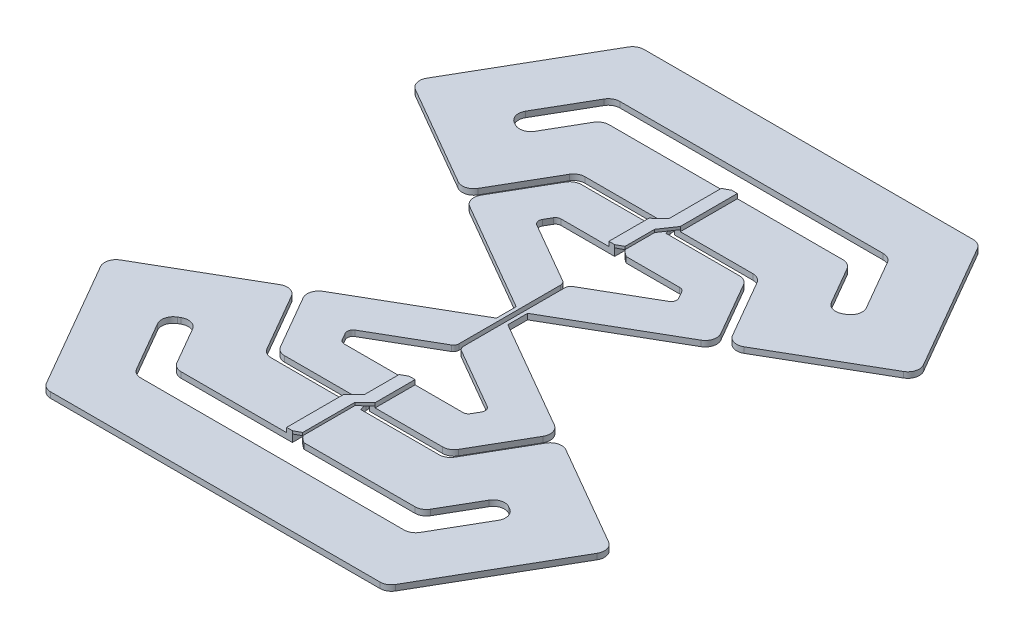
SolidWorks part; units mm, degrees
ref_plane "前视基准面" through (0, 0, 0) normal (0, 0, 1) x (1, 0, 0)
ref_plane "上视基准面" through (0, 0, 0) normal (0, 1, 0) x (1, 0, 0)
ref_plane "右视基准面" through (0, 0, 0) normal (1, 0, 0) x (0, 0, -1)
ref_plane "基准面1" through (0, 1, 0) normal (0, 1, 0) x (1, 0, 0)
ref_plane "基准面2" through (0, 1.3, 0) normal (0, 1, 0) x (1, 0, 0)
sketch "草图2" plane through (0, 0, 0) normal (0, 1, 0) x (1, 0, 0)
  line L0 (0, 9.4884) -> (0, -9.4884) construction
  line L1 (-1, -38.8119) -> (-1, 41.1881)
  line L3 (-1, 41.1881) -> (1, 41.1881)
  line L4 (1, -38.8119) -> (1, 41.1881)
  line L5 (-2.6411, -108.7811) -> (1, 41.1881) construction
  line L6 (-1, 41.1881) -> (2.6411, -108.7811) construction
  line L7 (-1, -38.8119) -> (1, -38.8119)
  point P1 (0, 0)
  point P4 (0, 0)
  dimension "D1" = 2
  dimension "D2" = 80
sketch "草图3" plane through (0, 0, 0) normal (0, 1, 0) x (1, 0, 0)
  line L0 (29.8397, 32.2391) -> (24.8038, 40.9615)
  line L1 (43.5, 28.5788) -> (30.5774, 50.9615)
  line L2 (28.8453, 51.9615) -> (-28.8453, 51.9615)
  line L3 (-30.5774, 50.9615) -> (-43.5, 28.5788)
  line L4 (-43.5, -28.5788) -> (-30.5774, -50.9615)
  line L5 (-28.8453, -51.9615) -> (28.8453, -51.9615)
  line L6 (30.5774, -50.9615) -> (43.5, -28.5788)
  line L7 (23, 12.1244) -> (22.5, 12.9904)
  line L8 (13.8453, 25.9808) -> (-13.8453, 25.9808)
  line L9 (-15.5774, 24.9808) -> (-21, 15.5885)
  line L10 (-21, -15.5885) -> (-15.5774, -24.9808)
  line L11 (-13.8453, -25.9808) -> (13.8453, -25.9808)
  line L12 (15.5774, -24.9808) -> (21, -15.5885)
  line L13 (0, 0) -> (0, 74.3259) construction
  line L14 (21, 15.5885) -> (15.5774, 24.9808)
  line L15 (45.5, -25.1147) -> (45.4917, -25.1099)
  line L16 (20.2679, -12.8564) -> (0, -1.1547)
  line L17 (-16.4434, 26.4808) -> (-22.299, 16.3385)
  line L18 (-22.299, -16.3385) -> (-16.4434, -26.4808)
  line L19 (-14.7113, -27.4808) -> (14.7113, -27.4808)
  line L20 (16.4434, -26.4808) -> (22.299, -16.3385)
  line L21 (22.299, 16.3385) -> (16.4434, 26.4808)
  line L22 (14.7113, 27.4808) -> (-14.7113, 27.4808)
  line L23 (42.7679, -25.8468) -> (25.0311, -15.6064)
  line L24 (-42.7679, -25.8468) -> (-25.0311, -15.6064)
  line L25 (22.9833, 12.1147) -> (23, 12.1244)
  line L26 (0, 1.1547) -> (20.2679, 12.8564)
  line L27 (-31.7321, 0) -> (-15.866, -27.4808) construction
  line L28 (-30, 0) -> (-15, -25.9808) construction
  line L29 (-15, 25.9808) -> (-30, 0) construction
  line L30 (-15.866, 27.4808) -> (-31.7321, 0) construction
  line L31 (23, -12.1244) -> (22.9833, -12.1147)
  line L32 (31.7321, 0) -> (15.866, 27.4808) construction
  line L33 (30, 0) -> (15, 25.9808) construction
  line L34 (15.866, -27.4808) -> (31.7321, 0) construction
  line L35 (15, -25.9808) -> (30, 0) construction
  line L36 (45.4917, 25.1099) -> (45.5, 25.1147)
  line L37 (-20.2679, -12.8564) -> (0, -1.1547)
  line L38 (-22.9833, 12.1147) -> (-23, 12.1244)
  line L39 (0, 0) -> (1, -0.5774)
  line L40 (0, 1.1547) -> (-20.2679, 12.8564)
  line L41 (25.0311, 15.6064) -> (42.7679, 25.8468)
  line L42 (-25.0311, 15.6064) -> (-42.7679, 25.8468)
  line L43 (-45.4917, 25.1099) -> (-45.5, 25.1147)
  line L44 (23.0718, 41.9615) -> (-23.0718, 41.9615)
  line L45 (-24.8038, 40.9615) -> (-29.8397, 32.2391)
  line L46 (-28.6913, 29.2667) -> (-29.1077, 29.507)
  line L47 (-22.2169, 36.4808) -> (-25.9593, 29.9987)
  line L48 (20.4848, 37.4808) -> (-20.4848, 37.4808)
  line L49 (25.9593, 29.9987) -> (22.2169, 36.4808)
  line L50 (28.6913, 29.2667) -> (29.1077, 29.507)
  line L51 (29.1077, -29.507) -> (28.6913, -29.2667)
  line L52 (22.2169, -36.4808) -> (25.9593, -29.9987)
  line L53 (-20.4848, -37.4808) -> (20.4848, -37.4808)
  line L54 (-25.9593, -29.9987) -> (-22.2169, -36.4808)
  line L55 (-29.1077, -29.507) -> (-28.6913, -29.2667)
  line L56 (-29.8397, -32.2391) -> (-24.8038, -40.9615)
  line L57 (-23.0718, -41.9615) -> (23.0718, -41.9615)
  line L58 (24.8038, -40.9615) -> (29.8397, -32.2391)
  line L59 (-11.5718, -15.9186) -> (0, -9.2376)
  line L60 (11.5718, -15.9186) -> (0, -9.2376)
  line L61 (11.2472, -18.4808) -> (11.9378, -17.2846)
  line L62 (-10.3812, -18.9808) -> (10.3812, -18.9808)
  line L63 (-11.9378, -17.2846) -> (-11.2472, -18.4808)
  line L64 (10.3812, 18.9808) -> (-10.3812, 18.9808)
  line L65 (-11.2472, 18.4808) -> (-11.9378, 17.2846)
  line L66 (0, 9.2376) -> (-11.5718, 15.9186)
  line L67 (0, 9.2376) -> (11.5718, 15.9186)
  line L68 (11.9378, 17.2846) -> (11.2472, 18.4808)
  line L69 (-30, 51.9615) -> (-44.5, 26.8468) construction
  line L70 (30, 51.9615) -> (-30, 51.9615) construction
  line L71 (-23.299, 14.6064) -> (-44.5, 26.8468) construction
  line L72 (44.5, 26.8468) -> (30, 51.9615) construction
  line L73 (23.299, 14.6064) -> (44.5, 26.8468) construction
  line L74 (26.9593, 28.2667) -> (30.8397, 30.507) construction
  line L75 (30.8397, 30.507) -> (24.2265, 41.9615) construction
  line L76 (26.9593, 28.2667) -> (21.6395, 37.4808) construction
  line L77 (24.2265, 41.9615) -> (-24.2265, 41.9615) construction
  line L78 (-24.2265, 41.9615) -> (-30.8397, 30.507) construction
  line L79 (-21.6395, 37.4808) -> (-26.9593, 28.2667) construction
  line L80 (21.6395, 37.4808) -> (-21.6395, 37.4808) construction
  line L81 (-26.9593, 28.2667) -> (-30.8397, 30.507) construction
  line L82 (-15.866, 27.4808) -> (-23.299, 14.6064) construction
  line L83 (15.866, 27.4808) -> (-15.866, 27.4808) construction
  line L84 (-15, 25.9808) -> (-22, 13.8564) construction
  line L85 (15, 25.9808) -> (-15, 25.9808) construction
  line L86 (22, 13.8564) -> (15, 25.9808) construction
  line L87 (23.299, 14.6064) -> (15.866, 27.4808) construction
  line L88 (0, 1.1547) -> (-22, 13.8564) construction
  line L89 (-23.299, -14.6064) -> (-15.866, -27.4808) construction
  line L90 (-44.5, -26.8468) -> (-23.299, -14.6064) construction
  line L91 (-44.5, -26.8468) -> (-30, -51.9615) construction
  line L92 (-30, -51.9615) -> (30, -51.9615) construction
  line L93 (30, -51.9615) -> (44.5, -26.8468) construction
  line L94 (44.5, -26.8468) -> (23.299, -14.6064) construction
  line L95 (15.866, -27.4808) -> (23.299, -14.6064) construction
  line L96 (-15.866, -27.4808) -> (15.866, -27.4808) construction
  line L97 (-30.8397, -30.507) -> (-26.9593, -28.2667) construction
  line L98 (-26.9593, -28.2667) -> (-21.6395, -37.4808) construction
  line L99 (-30.8397, -30.507) -> (-24.2265, -41.9615) construction
  line L100 (-21.6395, -37.4808) -> (21.6395, -37.4808) construction
  line L101 (21.6395, -37.4808) -> (26.9593, -28.2667) construction
  line L102 (30.8397, -30.507) -> (26.9593, -28.2667) construction
  line L103 (24.2265, -41.9615) -> (30.8397, -30.507) construction
  line L104 (-24.2265, -41.9615) -> (24.2265, -41.9615) construction
  line L105 (-22, -13.8564) -> (0, -1.1547) construction
  line L106 (-22, -13.8564) -> (-15, -25.9808) construction
  line L107 (15, -25.9808) -> (22, -13.8564) construction
  line L108 (22, -13.8564) -> (0, -1.1547) construction
  line L109 (-15, -25.9808) -> (15, -25.9808) construction
  line L110 (-12.4378, -16.4186) -> (-10.9585, -18.9808) construction
  line L111 (-12.4378, -16.4186) -> (0, -9.2376) construction
  line L112 (-10.9585, -18.9808) -> (10.9585, -18.9808) construction
  line L113 (10.9585, -18.9808) -> (12.4378, -16.4186) construction
  line L114 (12.4378, -16.4186) -> (0, -9.2376) construction
  line L115 (-10.9585, 18.9808) -> (-12.4378, 16.4186) construction
  line L116 (10.9585, 18.9808) -> (-10.9585, 18.9808) construction
  line L117 (0, 9.2376) -> (-12.4378, 16.4186) construction
  line L118 (12.4378, 16.4186) -> (10.9585, 18.9808) construction
  line L119 (0, 9.2376) -> (12.4378, 16.4186) construction
  line L120 (0, 1.1547) -> (22, 13.8564) construction
  circle A0 centre (0, 0) radius 51.9615 construction
  circle A1 centre (0, 0) radius 25.9808 construction
  arc A2 (-30.5774, 50.9615) -> (-28.8453, 51.9615) centre (-28.8453, 49.9615) cw
  arc A3 (-42.7679, 25.8468) -> (-43.5, 28.5788) centre (-41.7679, 27.5788) cw
  arc A4 (30.5774, 50.9615) -> (28.8453, 51.9615) centre (28.8453, 49.9615) ccw
  arc A5 (42.7679, 25.8468) -> (43.5, 28.5788) centre (41.7679, 27.5788) ccw
  arc A6 (29.1077, 29.507) -> (29.8397, 32.2391) centre (28.1077, 31.2391) ccw
  arc A7 (25.9593, 29.9987) -> (28.6913, 29.2667) centre (27.6913, 30.9987) ccw
  arc A8 (23.0718, 41.9615) -> (24.8038, 40.9615) centre (23.0718, 39.9615) cw
  arc A9 (-24.8038, 40.9615) -> (-23.0718, 41.9615) centre (-23.0718, 39.9615) cw
  arc A10 (-22.2169, 36.4808) -> (-20.4848, 37.4808) centre (-20.4848, 35.4808) cw
  arc A11 (20.4848, 37.4808) -> (22.2169, 36.4808) centre (20.4848, 35.4808) cw
  arc A12 (-28.6913, 29.2667) -> (-25.9593, 29.9987) centre (-27.6913, 30.9987) ccw
  arc A13 (-29.8397, 32.2391) -> (-29.1077, 29.507) centre (-28.1077, 31.2391) ccw
  arc A14 (-16.4434, 26.4808) -> (-14.7113, 27.4808) centre (-14.7113, 25.4808) cw
  arc A15 (-15.5774, 24.9808) -> (-13.8453, 25.9808) centre (-13.8453, 23.9808) cw
  arc A16 (15.5774, 24.9808) -> (13.8453, 25.9808) centre (13.8453, 23.9808) ccw
  arc A17 (16.4434, 26.4808) -> (14.7113, 27.4808) centre (14.7113, 25.4808) ccw
  arc A18 (22.299, 16.3385) -> (25.0311, 15.6064) centre (24.0311, 17.3385) ccw
  arc A19 (-21, 15.5885) -> (-20.2679, 12.8564) centre (-19.2679, 14.5885) ccw
  arc A20 (-25.0311, 15.6064) -> (-22.299, 16.3385) centre (-24.0311, 17.3385) ccw
  arc A21 (-22.299, -16.3385) -> (-25.0311, -15.6064) centre (-24.0311, -17.3385) ccw
  arc A22 (-43.5, -28.5788) -> (-42.7679, -25.8468) centre (-41.7679, -27.5788) cw
  arc A23 (-30.5774, -50.9615) -> (-28.8453, -51.9615) centre (-28.8453, -49.9615) ccw
  arc A24 (30.5774, -50.9615) -> (28.8453, -51.9615) centre (28.8453, -49.9615) cw
  arc A25 (43.5, -28.5788) -> (42.7679, -25.8468) centre (41.7679, -27.5788) ccw
  arc A26 (22.299, -16.3385) -> (25.0311, -15.6064) centre (24.0311, -17.3385) cw
  arc A27 (16.4434, -26.4808) -> (14.7113, -27.4808) centre (14.7113, -25.4808) cw
  arc A28 (-16.4434, -26.4808) -> (-14.7113, -27.4808) centre (-14.7113, -25.4808) ccw
  arc A29 (-28.6913, -29.2667) -> (-25.9593, -29.9987) centre (-27.6913, -30.9987) cw
  arc A30 (-29.1077, -29.507) -> (-29.8397, -32.2391) centre (-28.1077, -31.2391) ccw
  arc A31 (-22.2169, -36.4808) -> (-20.4848, -37.4808) centre (-20.4848, -35.4808) ccw
  arc A32 (22.2169, -36.4808) -> (20.4848, -37.4808) centre (20.4848, -35.4808) cw
  arc A33 (25.9593, -29.9987) -> (28.6913, -29.2667) centre (27.6913, -30.9987) cw
  arc A34 (29.8397, -32.2391) -> (29.1077, -29.507) centre (28.1077, -31.2391) ccw
  arc A35 (23.0718, -41.9615) -> (24.8038, -40.9615) centre (23.0718, -39.9615) ccw
  arc A36 (-24.8038, -40.9615) -> (-23.0718, -41.9615) centre (-23.0718, -39.9615) ccw
  arc A37 (-20.2679, -12.8564) -> (-21, -15.5885) centre (-19.2679, -14.5885) ccw
  arc A38 (21, -15.5885) -> (20.2679, -12.8564) centre (19.2679, -14.5885) ccw
  arc A39 (13.8453, -25.9808) -> (15.5774, -24.9808) centre (13.8453, -23.9808) ccw
  arc A40 (-15.5774, -24.9808) -> (-13.8453, -25.9808) centre (-13.8453, -23.9808) ccw
  arc A41 (-11.9378, -17.2846) -> (-11.5718, -15.9186) centre (-11.0718, -16.7846) cw
  arc A42 (-11.2472, -18.4808) -> (-10.3812, -18.9808) centre (-10.3812, -17.9808) ccw
  arc A43 (11.2472, -18.4808) -> (10.3812, -18.9808) centre (10.3812, -17.9808) cw
  arc A44 (11.5718, -15.9186) -> (11.9378, -17.2846) centre (11.0718, -16.7846) cw
  arc A45 (-11.2472, 18.4808) -> (-10.3812, 18.9808) centre (-10.3812, 17.9808) cw
  arc A46 (-11.9378, 17.2846) -> (-11.5718, 15.9186) centre (-11.0718, 16.7846) ccw
  arc A47 (11.9378, 17.2846) -> (11.5718, 15.9186) centre (11.0718, 16.7846) cw
  arc A48 (10.3812, 18.9808) -> (11.2472, 18.4808) centre (10.3812, 17.9808) cw
  arc A49 (21, 15.5885) -> (20.2679, 12.8564) centre (19.2679, 14.5885) cw
  point P187 (22, -13.8564)
  dimension "D8" = 2
  dimension "D9" = 2
  dimension "D10" = 2
  dimension "D11" = 2
  dimension "D12" = 2
  dimension "D13" = 2
  dimension "D14" = 2
  dimension "D15" = 2
  dimension "D16" = 2
  dimension "D17" = 2
  dimension "D18" = 2
  dimension "D19" = 2
  dimension "D20" = 2
  dimension "D21" = 2
  dimension "D22" = 2
  dimension "D23" = 2
  dimension "D24" = 2
  dimension "D25" = 2
  dimension "D26" = 2
  dimension "D27" = 2
  dimension "D28" = 2
  dimension "D29" = 2
  dimension "D30" = 2
  dimension "D31" = 2
  dimension "D32" = 2
  dimension "D33" = 2
  dimension "D34" = 2
  dimension "D35" = 2
  dimension "D36" = 2
  dimension "D37" = 2
  dimension "D38" = 2
  dimension "D39" = 2
  dimension "D40" = 2
  dimension "D41" = 2
  dimension "D42" = 2
  dimension "D43" = 2
  dimension "D44" = 2
  dimension "D45" = 2
  dimension "D46" = 2
  dimension "D47" = 1
  dimension "D48" = 1
  dimension "D49" = 1
  dimension "D50" = 1
  dimension "D51" = 1
  dimension "D52" = 1
  dimension "D53" = 1
  dimension "D54" = 1
  dimension "D55" = 2
  dimension "D3" = 10
  dimension "D5" = 10
  dimension "D4" = 1.5
  dimension "D6" = 7
  dimension "D7" = 7
extrude "凸台-拉伸6" add sketch "草图3" along normal blind 1 contours L40 L26 L14 L8 L9 L68 L67 L66 L65 L64 | L42 L17 L22 L21 L41 L1 L2 L3 L50 L49 L48 L47 L46 L45 L44 L0 | L37 L10 L11 L12 L16 L63 L59 L60 L61 L62 | L24 L4 L5 L6 L23 L20 L19 L18 L58 L57 L56 L55 L54 L53 L52 L51
extrude "切除-拉伸1" cut sketch "草图2" against normal blind 2 and the other way blind 2
sketch "草图4" plane through (0, 0, 0) normal (0, 1, 0) x (1, 0, 0)
  line L0 (0, 0) -> (0, 10.9591) construction
  line L1 (-1, 9.815) -> (-0.8888, 9.7507)
  line L2 (-0.3888, 8.8847) -> (-0.3888, -8.8847)
  line L3 (-1, -9.815) -> (-0.8888, -9.7507)
  line L4 (-1, -1.7321) -> (-1, 1.7321)
  line L5 (-1, 1.7321) -> (-1, 9.815)
  line L6 (-1, -1.7321) -> (-1, -9.815)
  line L7 (0.3888, 8.8847) -> (0.3888, -8.8847)
  line L8 (1, 9.815) -> (0.8888, 9.7507)
  line L9 (1, -9.815) -> (0.8888, -9.7507)
  line L10 (1, 9.815) -> (1, 1.7321)
  line L11 (1, 1.7321) -> (1, -1.7321)
  line L12 (1, -1.7321) -> (1, -9.815)
  line L13 (-1, 37.4808) -> (-0.4152, 37.0445)
  line L14 (0.3888, 35.4415) -> (0.3888, 27.8778)
  line L15 (0.5405, 27.1138) -> (1, 26.0021)
  line L16 (1, 18.9808) -> (0.403, 19.4261)
  line L17 (-0.5414, 26.3714) -> (-1, 27.4808)
  line L18 (-1, 37.4808) -> (-1, 27.4808)
  line L19 (1, 26.0021) -> (1, 18.9808)
  line L20 (-0.401, 21.034) -> (-0.3898, 25.6025)
  line L21 (-1, -18.9808) -> (-0.2298, -19.5554)
  line L22 (1, -37.4808) -> (0.4077, -37.0388)
  line L23 (0.5742, -21.1584) -> (0.5742, -25.7024)
  line L24 (0.6502, -26.2486) -> (1, -27.4808)
  line L25 (-0.3963, -35.4358) -> (-0.3963, -27.8681)
  line L26 (-0.5409, -27.1214) -> (-1, -25.9808)
  line L27 (-13.8453, -25.9808) -> (-1, -25.9808) construction
  line L28 (-1, -25.9808) -> (-1, -18.9808)
  line L30 (1, -27.4808) -> (1, -37.4808)
  arc A0 (0.3888, 27.8778) -> (0.5405, 27.1138) centre (2.3888, 27.8778) ccw
  arc A1 (-0.5414, 26.3714) -> (-0.3898, 25.6025) centre (-2.3898, 25.6074) cw
  arc A2 (0.403, 19.4261) -> (-0.401, 21.034) centre (1.599, 21.0291) cw
  arc A3 (0.3888, 35.4415) -> (-0.4152, 37.0445) centre (-1.6112, 35.4415) ccw
  arc A4 (0.5742, -21.1584) -> (-0.2298, -19.5554) centre (-1.4258, -21.1584) ccw
  arc A5 (-0.3963, -35.4358) -> (0.4077, -37.0388) centre (1.6037, -35.4358) ccw
  arc A6 (0.5742, -25.7024) -> (0.6502, -26.2486) centre (2.5742, -25.7024) ccw
  arc A7 (-0.3963, -27.8681) -> (-0.5409, -27.1214) centre (-2.3963, -27.8681) ccw
  arc A8 (0.8888, 9.7507) -> (0.3888, 8.8847) centre (1.3888, 8.8847) ccw
  arc A9 (-0.3888, 8.8847) -> (-0.8888, 9.7507) centre (-1.3888, 8.8847) ccw
  arc A10 (0.3888, -8.8847) -> (0.8888, -9.7507) centre (1.3888, -8.8847) ccw
  arc A11 (-0.3888, -8.8847) -> (-0.8888, -9.7507) centre (-1.3888, -8.8847) cw
  point P64 (0.3888, 9.4621)
  point P67 (-0.3888, 9.4621)
  point P70 (0.3888, -9.4621)
  point P73 (-0.3888, -9.4621)
  dimension "D1" = 2
  dimension "D2" = 2
  dimension "D3" = 2
  dimension "D4" = 2
  dimension "D5" = 2
  dimension "D6" = 2
  dimension "D7" = 2
  dimension "D8" = 2
  dimension "D9" = 1
  dimension "D10" = 1
  dimension "D11" = 1
  dimension "D12" = 1
extrude "凸台-拉伸7" add sketch "草图4" along normal blind 1
sketch "草图5" plane through (0, 1, 0) normal (0, 1, 0) x (1, 0, 0)
  line L0 (14.7113, 27.4808) -> (1, 27.4808) construction
  line L1 (1, 37.4808) -> (2, 37.4808)
  line L2 (1, 37.4808) -> (1, 27.4808)
  line L3 (1, 27.4808) -> (2, 27.4808)
  line L4 (2, 37.4808) -> (2, 27.4808)
  line L5 (-1, 18.9808) -> (-10.3812, 18.9808) construction
  line L6 (-1, 25.9808) -> (-2, 25.9808)
  line L7 (-1, 25.9808) -> (-1, 18.9808)
  line L8 (-1, 18.9808) -> (-2, 18.9808)
  line L9 (-2, 25.9808) -> (-2, 18.9808)
  line L10 (1, -25.9808) -> (13.8453, -25.9808) construction
  line L11 (1, -18.9808) -> (2, -18.9808)
  line L12 (1, -18.9808) -> (1, -25.9808)
  line L13 (1, -25.9808) -> (2, -25.9808)
  line L14 (2, -18.9808) -> (2, -25.9808)
  line L15 (-20.4848, -37.4808) -> (-1, -37.4808) construction
  line L16 (-1, -27.4808) -> (-2, -27.4808)
  line L17 (-1, -27.4808) -> (-1, -37.4808)
  line L18 (-1, -37.4808) -> (-2, -37.4808)
  line L19 (-2, -27.4808) -> (-2, -37.4808)
  dimension "D1" = 1
  dimension "D2" = 1
extrude "凸台-拉伸8" add sketch "草图5" along normal blind 0.8
sketch "草图6" plane through (0, 1.3, 0) normal (0, 1, 0) x (1, 0, 0)
  line L0 (1, 37.4808) -> (-0.1834, 36.8419)
  line L1 (-0.1834, 36.8419) -> (-0.1834, 27.7098)
  line L2 (-0.1834, 27.7098) -> (-2, 25.9808)
  line L3 (2, 27.4808) -> (0.1813, 24.8071)
  line L4 (0.1813, 24.8071) -> (0.1813, 19.6185)
  line L5 (-1, 18.9808) -> (0.1813, 19.6185)
  line L6 (1, -18.9808) -> (-0.1622, -19.6082)
  line L7 (-1, -37.4808) -> (0.1821, -36.8426)
  line L8 (0.1821, -36.8426) -> (0.1821, -27.7111)
  line L9 (0.1821, -27.7111) -> (2, -25.9808)
  line L10 (-0.1622, -19.6082) -> (-0.1622, -25.7315)
  line L11 (-0.1622, -25.7315) -> (-2, -27.4808)
  line L12 (1, -18.9808) -> (1, -25.9808)
  line L13 (1, -25.9808) -> (2, -25.9808)
  line L14 (-1, -37.4808) -> (-1, -27.4808)
  line L15 (-1, -27.4808) -> (-2, -27.4808)
  line L16 (1, 37.4808) -> (1, 27.4808)
  line L17 (1, 27.4808) -> (2, 27.4808)
  line L18 (-1, 18.9808) -> (-1, 25.9808)
  line L19 (-1, 25.9808) -> (-2, 25.9808)
  arc A0 (-0.401, 21.034) -> (0.403, 19.4261) centre (1.599, 21.0291) ccw construction
  arc A1 (0.3888, 35.4415) -> (-0.4152, 37.0445) centre (-1.6112, 35.4415) ccw construction
  arc A2 (0.5742, -21.1584) -> (-0.2298, -19.5554) centre (-1.4258, -21.1584) ccw construction
  arc A3 (-0.3963, -35.4358) -> (0.4077, -37.0388) centre (1.6037, -35.4358) ccw construction
extrude "凸台-拉伸9" add sketch "草图6" along normal blind 0.5
